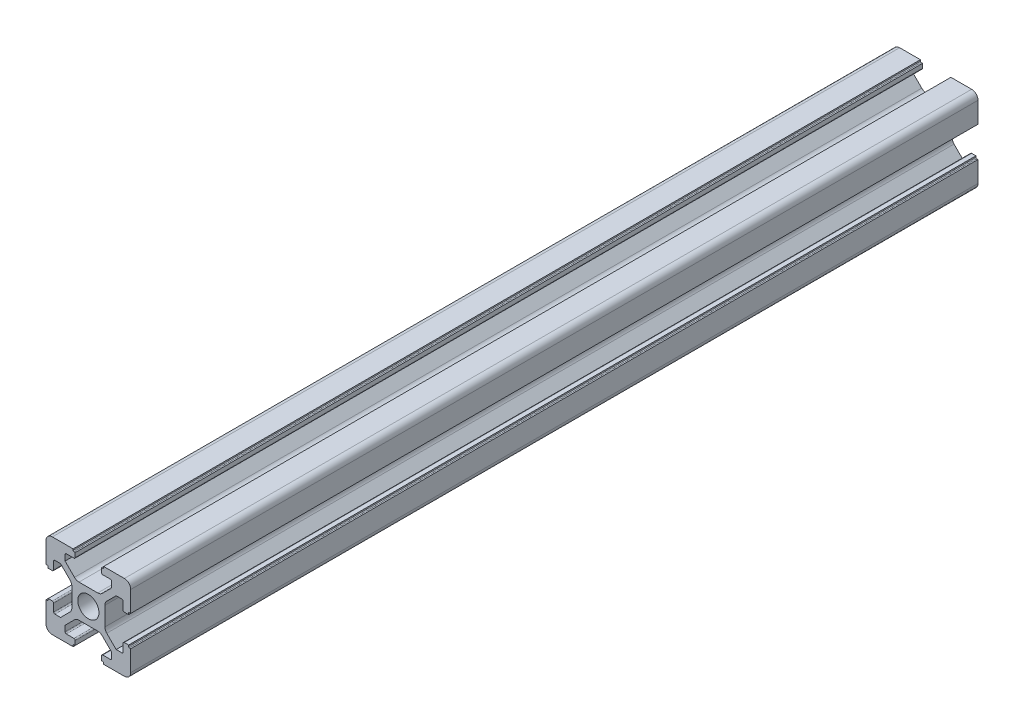
SolidWorks part; units mm, degrees
ref_plane "前视基准面" through (0, 0, 0) normal (0, 0, 1) x (1, 0, 0)
ref_plane "上视基准面" through (0, 0, 0) normal (0, 1, 0) x (1, 0, 0)
ref_plane "右视基准面" through (0, 0, 0) normal (1, 0, 0) x (0, 0, -1)
sketch "草图1" plane through (0, 0, 0) normal (0, 0, 1) x (1, 0, 0)
  line L0 (4.216, 3.2442) -> (6.4367, 5.4649)
  line L1 (6.4367, 5.4649) -> (7.7767, 5.4649)
  line L2 (8.0767, 5.1649) -> (8.0767, 3.3649)
  line L3 (8.3767, 3.0649) -> (9.3767, 3.0649)
  line L4 (9.3767, 3.0649) -> (9.3767, 3.3649)
  line L5 (9.5767, 3.5649) -> (9.8767, 3.5649)
  line L6 (9.8767, 3.5649) -> (9.8767, 8.4649)
  line L7 (8.3767, 9.9649) -> (3.4767, 9.9649)
  line L8 (3.4767, 9.9649) -> (3.4767, 9.6649)
  line L9 (3.2767, 9.4649) -> (2.9767, 9.4649)
  line L10 (2.9767, 9.4649) -> (2.9767, 8.4649)
  line L11 (3.2767, 8.1649) -> (5.0767, 8.1649)
  line L12 (5.3767, 7.8649) -> (5.3767, 6.5249)
  line L13 (5.3767, 6.5249) -> (3.156, 4.3042)
  line L14 (2.0953, 3.8649) -> (-2.342, 3.8649)
  line L15 (-3.4027, 4.3042) -> (-5.6233, 6.5249)
  line L16 (-5.6233, 6.5249) -> (-5.6233, 7.8649)
  line L17 (-5.3233, 8.1649) -> (-3.5233, 8.1649)
  line L18 (-3.2233, 8.4649) -> (-3.2233, 9.4649)
  line L19 (-3.2233, 9.4649) -> (-3.5233, 9.4649)
  line L20 (-3.7233, 9.6649) -> (-3.7233, 9.9649)
  line L21 (-3.7233, 9.9649) -> (-8.6233, 9.9649)
  line L22 (-10.1233, 8.4649) -> (-10.1233, 3.5649)
  line L23 (-10.1233, 3.5649) -> (-9.8233, 3.5649)
  line L24 (-9.6233, 3.3649) -> (-9.6233, 3.0649)
  line L25 (-9.6233, 3.0649) -> (-8.6233, 3.0649)
  line L26 (-8.3233, 3.3649) -> (-8.3233, 5.1649)
  line L27 (-8.0233, 5.4649) -> (-6.6833, 5.4649)
  line L28 (-6.6833, 5.4649) -> (-4.4627, 3.2442)
  line L29 (-4.0233, 2.1836) -> (-4.0233, -2.2538)
  line L30 (-4.4627, -3.3144) -> (-6.6833, -5.5351)
  line L31 (-6.6833, -5.5351) -> (-8.0233, -5.5351)
  line L32 (-8.3233, -5.2351) -> (-8.3233, -3.4351)
  line L33 (-8.6233, -3.1351) -> (-9.6233, -3.1351)
  line L34 (-9.6233, -3.1351) -> (-9.6233, -3.4351)
  line L35 (-9.8233, -3.6351) -> (-10.1233, -3.6351)
  line L36 (-10.1233, -3.6351) -> (-10.1233, -8.5351)
  line L37 (-8.6233, -10.0351) -> (-3.7233, -10.0351)
  line L38 (-3.7233, -10.0351) -> (-3.7233, -9.7351)
  line L39 (-3.5233, -9.5351) -> (-3.2233, -9.5351)
  line L40 (-3.2233, -9.5351) -> (-3.2233, -8.5351)
  line L41 (-3.5233, -8.2351) -> (-5.3233, -8.2351)
  line L42 (-5.6233, -7.9351) -> (-5.6233, -6.5951)
  line L43 (-5.6233, -6.5951) -> (-3.4027, -4.3744)
  line L44 (-2.342, -3.9351) -> (2.0953, -3.9351)
  line L45 (3.156, -4.3744) -> (5.3767, -6.5951)
  line L46 (5.3767, -6.5951) -> (5.3767, -7.9351)
  line L47 (5.0767, -8.2351) -> (3.2767, -8.2351)
  line L48 (2.9767, -8.5351) -> (2.9767, -9.5351)
  line L49 (2.9767, -9.5351) -> (3.2767, -9.5351)
  line L50 (3.4767, -9.7351) -> (3.4767, -10.0351)
  line L51 (3.4767, -10.0351) -> (8.3767, -10.0351)
  line L52 (9.8767, -8.5351) -> (9.8767, -3.6351)
  line L53 (9.8767, -3.6351) -> (9.5767, -3.6351)
  line L54 (9.3767, -3.4351) -> (9.3767, -3.1351)
  line L55 (9.3767, -3.1351) -> (8.3767, -3.1351)
  line L56 (8.0767, -3.4351) -> (8.0767, -5.2351)
  line L57 (7.7767, -5.5351) -> (6.4367, -5.5351)
  line L58 (6.4367, -5.5351) -> (4.216, -3.3144)
  line L59 (3.7767, -2.2538) -> (3.7767, 2.1836)
  circle A0 centre (-0.1233, -0.0351) radius 2.5
  arc A1 (8.0767, 5.1649) -> (7.7767, 5.4649) centre (7.7767, 5.1649) ccw
  arc A2 (8.0767, 3.3649) -> (8.3767, 3.0649) centre (8.3767, 3.3649) ccw
  arc A3 (9.5767, 3.5649) -> (9.3767, 3.3649) centre (9.5767, 3.3649) ccw
  arc A4 (9.8767, 8.4649) -> (8.3767, 9.9649) centre (8.3767, 8.4649) ccw
  arc A5 (3.2767, 9.4649) -> (3.4767, 9.6649) centre (3.2767, 9.6649) ccw
  arc A6 (2.9767, 8.4649) -> (3.2767, 8.1649) centre (3.2767, 8.4649) ccw
  arc A7 (5.3767, 7.8649) -> (5.0767, 8.1649) centre (5.0767, 7.8649) ccw
  arc A8 (2.0953, 3.8649) -> (3.156, 4.3042) centre (2.0953, 5.3649) ccw
  arc A9 (-3.4027, 4.3042) -> (-2.342, 3.8649) centre (-2.342, 5.3649) ccw
  arc A10 (-5.3233, 8.1649) -> (-5.6233, 7.8649) centre (-5.3233, 7.8649) ccw
  arc A11 (-3.5233, 8.1649) -> (-3.2233, 8.4649) centre (-3.5233, 8.4649) ccw
  arc A12 (-3.7233, 9.6649) -> (-3.5233, 9.4649) centre (-3.5233, 9.6649) ccw
  arc A13 (-8.6233, 9.9649) -> (-10.1233, 8.4649) centre (-8.6233, 8.4649) ccw
  arc A14 (-9.6233, 3.3649) -> (-9.8233, 3.5649) centre (-9.8233, 3.3649) ccw
  arc A15 (-8.6233, 3.0649) -> (-8.3233, 3.3649) centre (-8.6233, 3.3649) ccw
  arc A16 (-8.0233, 5.4649) -> (-8.3233, 5.1649) centre (-8.0233, 5.1649) ccw
  arc A17 (-4.0233, 2.1836) -> (-4.4627, 3.2442) centre (-5.5233, 2.1836) ccw
  arc A18 (-4.4627, -3.3144) -> (-4.0233, -2.2538) centre (-5.5233, -2.2538) ccw
  arc A19 (-8.3233, -5.2351) -> (-8.0233, -5.5351) centre (-8.0233, -5.2351) ccw
  arc A20 (-8.3233, -3.4351) -> (-8.6233, -3.1351) centre (-8.6233, -3.4351) ccw
  arc A21 (-9.8233, -3.6351) -> (-9.6233, -3.4351) centre (-9.8233, -3.4351) ccw
  arc A22 (-10.1233, -8.5351) -> (-8.6233, -10.0351) centre (-8.6233, -8.5351) ccw
  arc A23 (-3.5233, -9.5351) -> (-3.7233, -9.7351) centre (-3.5233, -9.7351) ccw
  arc A24 (-3.2233, -8.5351) -> (-3.5233, -8.2351) centre (-3.5233, -8.5351) ccw
  arc A25 (-5.6233, -7.9351) -> (-5.3233, -8.2351) centre (-5.3233, -7.9351) ccw
  arc A26 (-2.342, -3.9351) -> (-3.4027, -4.3744) centre (-2.342, -5.4351) ccw
  arc A27 (3.156, -4.3744) -> (2.0953, -3.9351) centre (2.0953, -5.4351) ccw
  arc A28 (5.0767, -8.2351) -> (5.3767, -7.9351) centre (5.0767, -7.9351) ccw
  arc A29 (3.2767, -8.2351) -> (2.9767, -8.5351) centre (3.2767, -8.5351) ccw
  arc A30 (3.4767, -9.7351) -> (3.2767, -9.5351) centre (3.2767, -9.7351) ccw
  arc A31 (8.3767, -10.0351) -> (9.8767, -8.5351) centre (8.3767, -8.5351) ccw
  arc A32 (9.3767, -3.4351) -> (9.5767, -3.6351) centre (9.5767, -3.4351) ccw
  arc A33 (8.3767, -3.1351) -> (8.0767, -3.4351) centre (8.3767, -3.4351) ccw
  arc A34 (7.7767, -5.5351) -> (8.0767, -5.2351) centre (7.7767, -5.2351) ccw
  arc A35 (3.7767, -2.2538) -> (4.216, -3.3144) centre (5.2767, -2.2538) ccw
  arc A36 (4.216, 3.2442) -> (3.7767, 2.1836) centre (5.2767, 2.1836) ccw
extrude "凸台-拉伸1" add sketch "草图1" along normal blind 200
